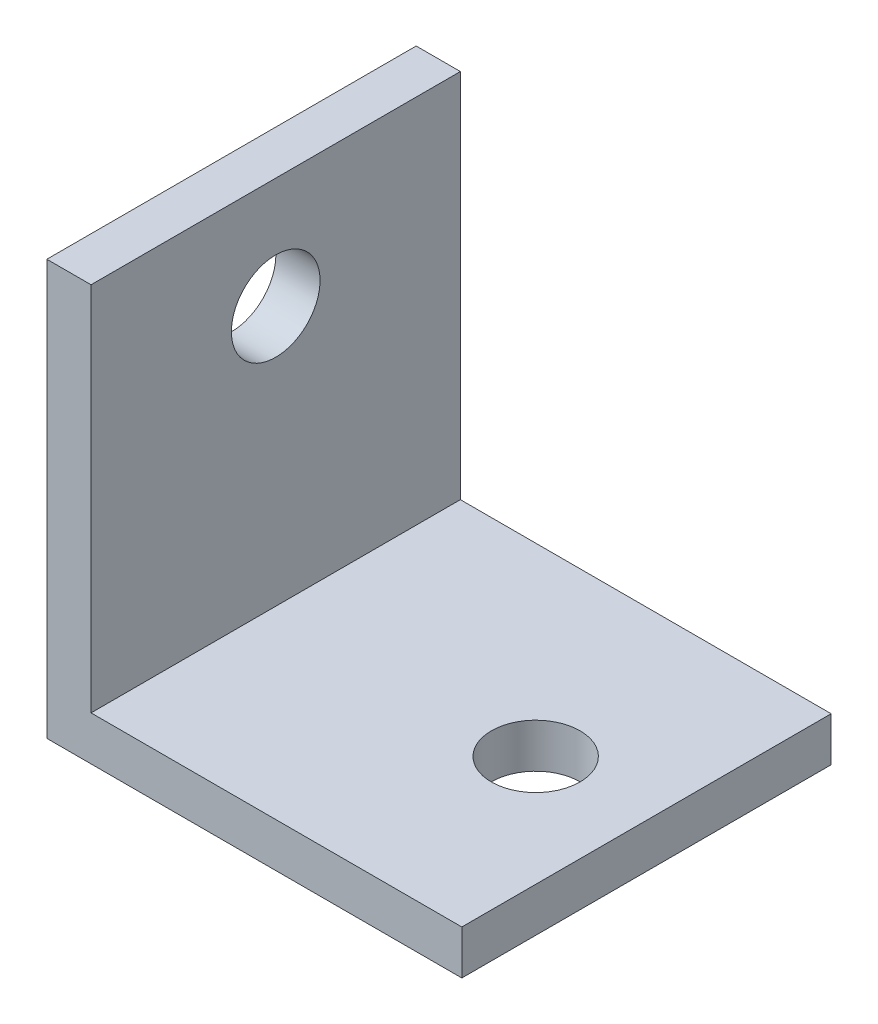
SolidWorks part; units mm, degrees
ref_plane "Plan de face" through (0, 0, 0) normal (0, 0, 1) x (1, 0, 0)
ref_plane "Plan de dessus" through (0, 0, 0) normal (0, 1, 0) x (1, 0, 0)
ref_plane "Plan de droite" through (0, 0, 0) normal (1, 0, 0) x (0, 0, -1)
sketch "Esquisse1" plane through (0, 0, 0) normal (0, 0, 1) x (1, 0, 0)
  line L0 (0, 0) -> (14.27, 0)
  line L1 (14.27, 0) -> (14.27, 1.52)
  line L2 (14.27, 1.52) -> (1.52, 1.52)
  line L3 (1.52, 1.52) -> (1.52, 14.27)
  line L4 (1.52, 14.27) -> (0, 14.27)
  line L5 (0, 14.27) -> (0, 0)
  dimension "D1" = 1.52
  dimension "D2" = 1.52
  dimension "D3" = 14.27
  dimension "D4" = 14.27
extrude "Boss.-Extru.1" add sketch "Esquisse1" along normal blind 12.7
sketch "Esquisse2" plane through (1.52, 0, 0) normal (1, 0, 0) x (0, 0, -1)
  line L0 (-12.7, 0) -> (0, 0) construction
  circle A0 centre (-6.35, 10.46) radius 1.525
  dimension "D1" = 3.05
  dimension "D2" = 10.46
extrude "Enlèv. mat.-Extru.1" cut sketch "Esquisse2" against normal blind 12.7
sketch "Esquisse3" plane through (0, 1.52, 0) normal (0, 1, 0) x (1, 0, 0)
  line L0 (0, -12.7) -> (0, 0) construction
  circle A0 centre (10.46, -6.35) radius 1.525
  point P2 (0, 0)
  dimension "D1" = 3.05
  dimension "D2" = 10.46
extrude "Enlèv. mat.-Extru.2" cut sketch "Esquisse3" against normal blind 12.7
